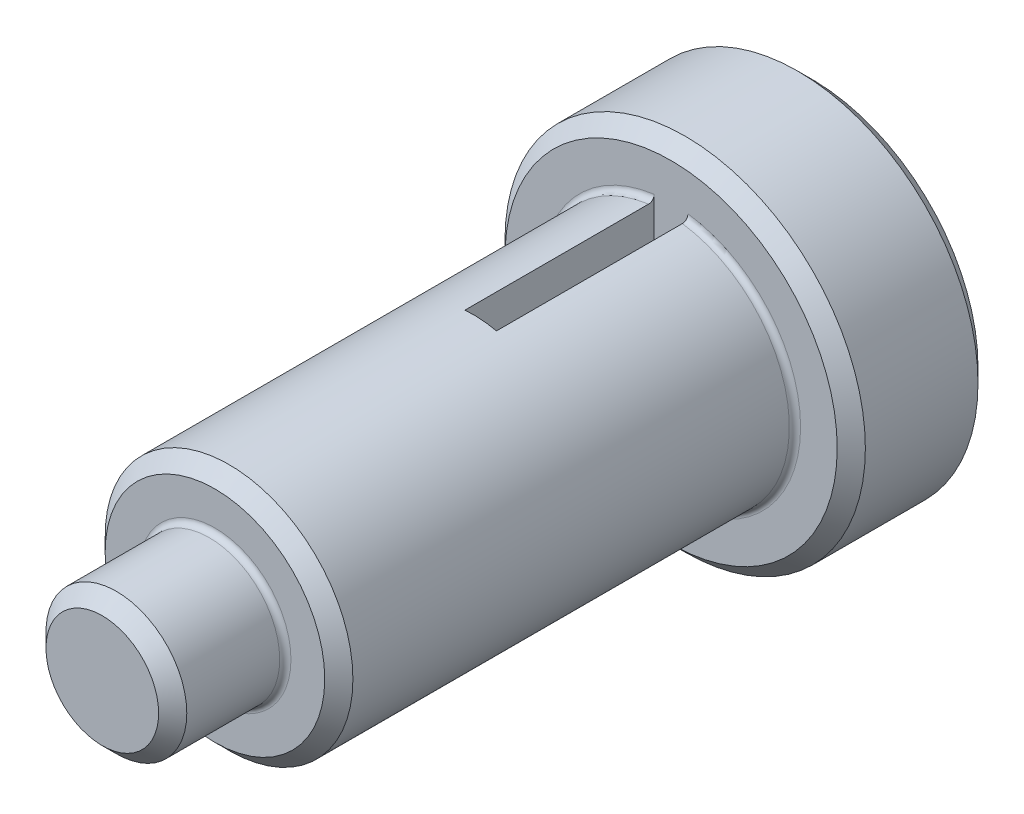
SolidWorks part; units mm, degrees
ref_plane "Front Plane" through (0, 0, 0) normal (0, 0, 1) x (1, 0, 0)
ref_plane "Top Plane" through (0, 0, 0) normal (0, 1, 0) x (1, 0, 0)
ref_plane "Right Plane" through (0, 0, 0) normal (1, 0, 0) x (0, 0, -1)
sketch "Sketch1" plane through (0, 0, 0) normal (0, 0, 1) x (1, 0, 0)
  circle A0 centre (0, 0) radius 32
  dimension "D1" = 64
extrude "Boss-Extrude1" add sketch "Sketch1" along normal blind 25
sketch "Sketch2" plane through (0, 0, 25) normal (0, 0, 1) x (1, 0, 0)
  circle A0 centre (0, 0) radius 22
  dimension "D1" = 44
extrude "Boss-Extrude2" add sketch "Sketch2" along normal blind 81
sketch "Sketch3" plane through (0, 0, 106) normal (0, 0, 1) x (1, 0, 0)
  circle A0 centre (0, 0) radius 12.5
  dimension "D1" = 25
extrude "Boss-Extrude3" add sketch "Sketch3" along normal blind 20
sketch "Sketch4" plane through (0, 0, 0) normal (0, 0, -1) x (-1, 0, 0)
  circle A0 centre (0, 0) radius 16
  dimension "D1" = 32
extrude "Cut-Extrude1" cut sketch "Sketch4" against normal blind 77
ref_plane "Plane1" through (0, 32, 0) normal (0, 1, 0) x (1, 0, 0)
sketch "Sketch5" plane through (0, 32, 0) normal (0, 1, 0) x (1, 0, 0)
  line L0 (0, 0) -> (0, -106) construction
  line L1 (-12.5, -106) -> (12.5, -106) construction
  line L2 (3, -25) -> (3, -59)
  line L3 (-22, -25) -> (22, -25) construction
  line L4 (3, -59) -> (-3, -58.6015)
  line L5 (-3, -58.6015) -> (-3, -25)
  line L6 (-3, -25) -> (3, -25)
  dimension "D1" = 34
  dimension "D2" = 3
  dimension "D3" = 3
  dimension "D4" = 93.8
extrude "Cut-Extrude2" cut sketch "Sketch5" against normal through all
chamfer "Chamfer1" distance 2.5 angle 45 4 edges at (12.5, 0, 126) (22, 0, 106) (32, 0, 25) (32, 0, 0)
fillet "Fillet1" radius 1 3 edges at (12.5, 0, 106) (22, 0, 25) (-22, 0, 25)
